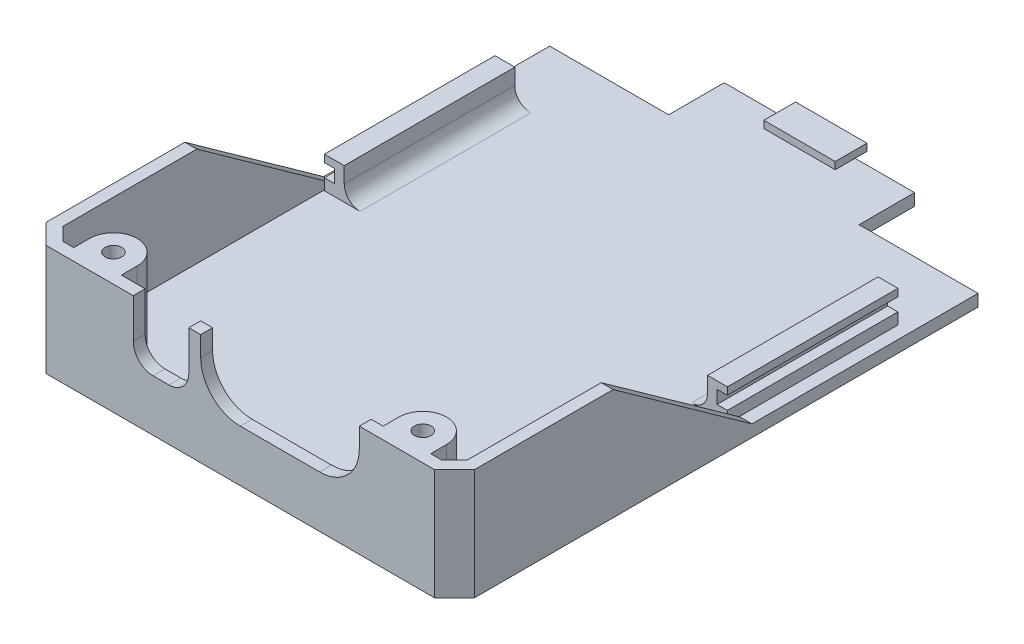
SolidWorks part; units mm, degrees
ref_plane "Alzado" through (0, 0, 0) normal (0, 0, 1) x (1, 0, 0)
ref_plane "Planta" through (0, 0, 0) normal (0, 1, 0) x (1, 0, 0)
ref_plane "Vista lateral" through (0, 0, 0) normal (1, 0, 0) x (0, 0, -1)
sketch "Croquis1" plane through (0, 0, 0) normal (0, 1, 0) x (1, 0, 0)
  line L0 (-24, 60) -> (24, 60)
  line L1 (54, 46) -> (54, -81)
  line L2 (54, -81) -> (49, -86)
  line L3 (49, -86) -> (-49, -86)
  line L4 (-49, -86) -> (-54, -81)
  line L5 (-54, -81) -> (-54, 46)
  line L6 (24, 60) -> (24, 46)
  line L7 (24, 46) -> (54, 46)
  line L8 (-24, 60) -> (-24, 46)
  line L9 (-24, 46) -> (-54, 46)
  line L10 (0, 0) -> (0, 131.1963) construction
  line L11 (0, -86) -> (0, -64.2759) construction
  circle A0 centre (-39, -79) radius 3.75
  circle A1 centre (39, -79) radius 3.75
  point P3 (0, 60)
  point P8 (0, -86)
  dimension "D7" = 7
  dimension "D8" = 15
  dimension "D9" = 7.5
  dimension "D1" = 108
  dimension "D2" = 146
  dimension "D3" = 14
  dimension "D4" = 48
  dimension "D5" = 60
  dimension "D6" = 98
extrude "Saliente-Extruir1" add sketch "Croquis1" along normal blind 3
sketch "Croquis6" plane through (0, 0, -46) normal (0, 0, -1) x (-1, 0, 0)
  line L0 (50.8, 3) -> (50.8, 5.85)
  line L1 (24, 3) -> (54, 3) construction
  line L2 (50.8, 11) -> (45.8, 11)
  line L3 (45.8, 11) -> (45.8, 7)
  line L4 (47.8, 3) -> (50.8, 3)
  line L8 (50.8, 9.15) -> (48.2, 9.15)
  line L12 (50.8, 9.15) -> (50.8, 11)
  line L14 (54, 3) -> (54, 0) construction
  line L15 (47.8, 3) -> (41.8, 3)
  line L16 (48.2, 9.15) -> (48.2, 5.85)
  line L17 (48.2, 5.85) -> (50.8, 5.85)
  line L18 (48.2, 7.5) -> (52.9876, 7.5) construction
  arc A0 (45.8, 7) -> (41.8, 3) centre (41.8, 7) cw
  dimension "D3" = 4
  dimension "D1" = 3.2
  dimension "D2" = 5
  dimension "D4" = 4.5
  dimension "D5" = 3.3
  dimension "D6" = 2.6
  dimension "D8" = 8
extrude "Saliente-Extruir5" add sketch "Croquis6" against normal blind 43 from offset 17 offset against normal yes
sketch "Croquis3" plane through (-54, 0, 0) normal (-1, 0, 0) x (0, 0, 1)
  line L0 (11, 3) -> (46, 28)
  line L1 (-46, 3) -> (81, 3) construction
  line L2 (46, 28) -> (79.2074, 28)
  line L3 (79.2074, 28) -> (79.2074, 3)
  line L4 (79.2074, 3) -> (11, 3)
  line L7 (86, 3) -> (86, 0) construction
  dimension "D1" = 75
  dimension "D2" = 25
  dimension "D3" = 40
extrude "Saliente-Extruir3" add sketch "Croquis3" against normal blind 3
sketch "Croquis4" plane through (0, 3, 0) normal (0, 1, 0) x (1, 0, 0)
  line L0 (0, 0) -> (0, -99.9539) construction
  line L1 (-54, -79.2074) -> (-54, -81)
  line L2 (-54, -81) -> (-49, -86)
  line L3 (-49, -86) -> (0, -86)
  line L4 (-49, -86) -> (49, -86) construction
  line L7 (-47.7574, -83) -> (-45, -83)
  line L11 (-51, -79.7574) -> (-51, -79.2074)
  line L13 (-39, -79) -> (-39, -83) construction
  line L16 (-51, -79.7574) -> (-47.7574, -83)
  line L17 (-54, -79.2074) -> (-51, -79.2074)
  line L18 (0, -83) -> (0, -86)
  line L19 (-33, -79) -> (-33, -83)
  line L20 (-45, -79) -> (-45, -83)
  line L22 (-33, -83) -> (0, -83)
  circle A1 centre (-39, -79) radius 3.75
  arc A4 (-33, -79) -> (-45, -79) centre (-39, -79) ccw
  circle A6 centre (-39, -79) radius 3.75 construction
  dimension "D1" = 3
  dimension "D2" = 3
  dimension "D8" = 6
extrude "Saliente-Extruir4" add sketch "Croquis4" along normal up to surface (25 mm away) up to face at (-52.5, 28, 62.6037)
sketch "Croquis8" plane through (0, 28, 0) normal (0, 1, 0) x (1, 0, 0)
  circle A0 centre (-39, -79) radius 2.1
  circle A1 centre (-39, -79) radius 3.75
  circle A2 centre (-39, -79) radius 3.75 construction
  dimension "D1" = 4.2
extrude "Saliente-Extruir7" add sketch "Croquis8" against normal blind 3
sketch "Croquis11" plane through (0, 28, 0) normal (0, 1, 0) x (1, 0, 0)
  line L0 (-45, -83) -> (-33, -83)
  line L1 (-43.8734, -75.5) -> (-34.1266, -75.5)
  line L2 (-45, -79) -> (-45, -83) construction
  line L3 (-33, -79) -> (-33, -83) construction
  line L4 (-45, -79) -> (-45, -83)
  line L5 (-33, -79) -> (-33, -83)
  arc A0 (-33, -79) -> (-45, -79) centre (-39, -79) ccw construction
  arc A1 (-33, -79) -> (-45, -79) centre (-39, -79) ccw
  line M8 (-33, -83) -> (-33, -79)
  arc M9 (-33, -79) -> (-45, -79) centre (-39, -79) ccw
  line M10 (-45, -79) -> (-45, -83)
  circle M15 centre (-39, -79) radius 2.1
  dimension "D1" = 7.5
extrude "Saliente-Extruir8" [suppressed] add sketch "Croquis11" along normal blind 3 contours L1 L0 M9 M10 M8 M15
mirror "Simetría1" about plane through (0, 0, 0) normal (1, 0, 0) of "Saliente-Extruir8", "Saliente-Extruir5", "Saliente-Extruir4", "Saliente-Extruir3", "Saliente-Extruir7"
sketch "Croquis7" plane through (0, 3, 0) normal (0, 1, 0) x (1, 0, 0)
  line L0 (-9, 55) -> (9, 55)
  line L1 (9, 55) -> (9, 63)
  line L2 (9, 63) -> (-9, 63)
  line L3 (0, 55) -> (0, 83.7528) construction
  line L5 (-9, 55) -> (-9, 63)
  line L6 (24, 60) -> (-24, 60) construction
  point P8 (0, 63)
  dimension "D1" = 5
  dimension "D2" = 3
  dimension "D3" = 18
extrude "Saliente-Extruir6" add sketch "Croquis7" along normal blind 1.8
sketch "Croquis9" plane through (0, 0, 86) normal (0, 0, 1) x (1, 0, 0)
  line L0 (-10, 28) -> (-10, 23)
  line L1 (-49, 28) -> (49, 28) construction
  line L2 (0, 13) -> (20, 13)
  line L3 (30, 23) -> (30, 28)
  line L4 (-49, 0) -> (49, 0) construction
  line L5 (-27, 28) -> (-27, 18)
  line L6 (-22, 13) -> (-18, 13)
  line L7 (-13, 18) -> (-13, 28)
  line L8 (-27, 28) -> (-13, 28)
  arc A0 (20, 13) -> (30, 23) centre (20, 23) ccw
  arc A1 (0, 13) -> (-10, 23) centre (0, 23) cw
  arc A2 (-18, 13) -> (-13, 18) centre (-18, 18) ccw
  arc A3 (-27, 18) -> (-22, 13) centre (-22, 18) ccw
  point P11 (10, 13)
  point P16 (0, 0)
  point P23 (-20, 28)
  line M5 (49, 28) -> (-49, 28)
  dimension "D1" = 10
  dimension "D5" = 5
  dimension "D2" = 15
  dimension "D3" = 40
  dimension "D4" = 10
  dimension "D6" = 20
  dimension "D7" = 14
extrude "Cortar-Extruir1" cut sketch "Croquis9" against normal blind 10 and the other way through all contours A1 L2 A0 L3 L0 M5 | L5 A3 L6 A2 L7 M5
